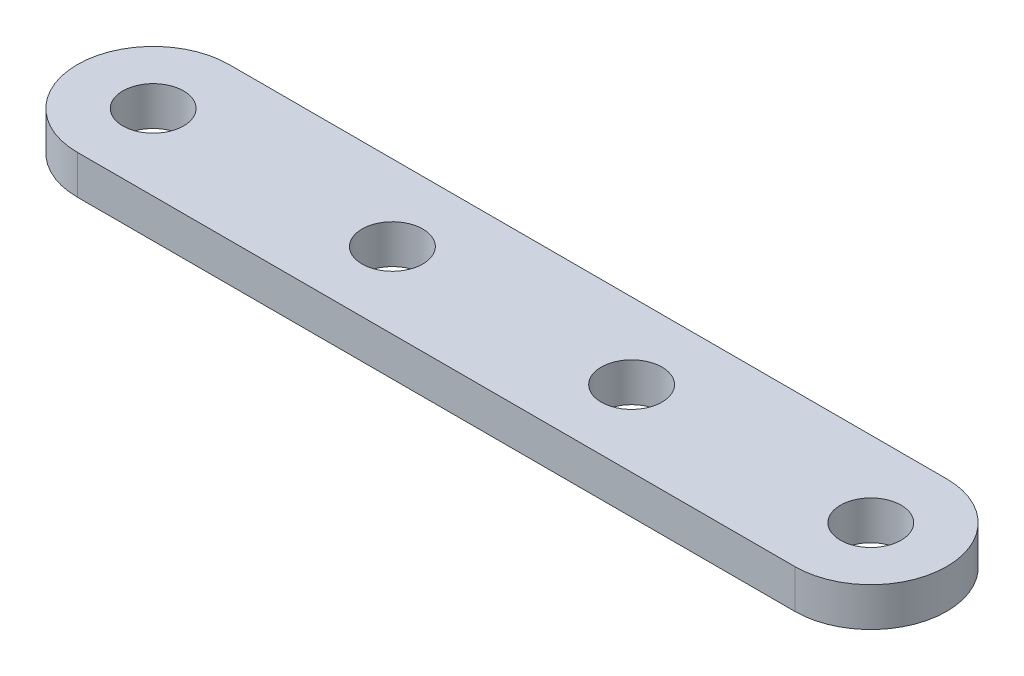
SolidWorks part; units mm, degrees
ref_plane "Front Plane" through (0, 0, 0) normal (0, 0, 1) x (1, 0, 0)
ref_plane "Top Plane" through (0, 0, 0) normal (0, 1, 0) x (1, 0, 0)
ref_plane "Right Plane" through (0, 0, 0) normal (1, 0, 0) x (0, 0, -1)
sketch "Sketch1" plane through (0, 0, 0) normal (0, 1, 0) x (1, 0, 0)
  line L0 (0, 0) -> (60, 0) construction
  line L1 (0, 6.35) -> (60, 6.35)
  line L2 (0, -6.35) -> (60, -6.35)
  circle A0 centre (0, 0) radius 2.54
  circle A1 centre (0, 0) radius 6.35 construction
  circle A2 centre (20, 0) radius 2.54
  circle A3 centre (20, 0) radius 6.35 construction
  circle A4 centre (40, 0) radius 2.54
  circle A5 centre (40, 0) radius 6.35 construction
  circle A6 centre (60, 0) radius 2.54
  circle A7 centre (60, 0) radius 6.35 construction
  arc A8 (0, 6.35) -> (0, -6.35) centre (0, 0) ccw
  arc A9 (60, -6.35) -> (60, 6.35) centre (60, 0) ccw
  point P5 (30, 0)
  dimension "D1" = 5.08
  dimension "D4" = 20
  dimension "D2" = 3.81
  dimension "D3" = 4
extrude "Boss-Extrude1" add sketch "Sketch1" along normal blind 3.25
